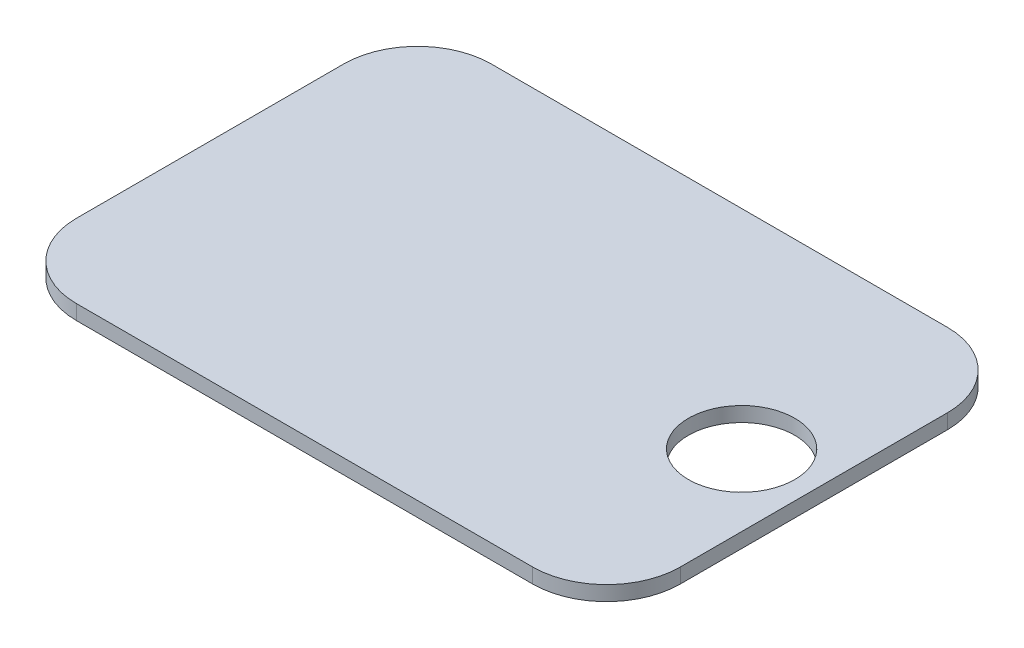
SolidWorks part; units mm, degrees
material "Acrylic (Medium-high impact)"
ref_plane "Front Plane" through (0, 0, 0) normal (0, 0, 1) x (1, 0, 0)
ref_plane "Top Plane" through (0, 0, 0) normal (0, 1, 0) x (1, 0, 0)
ref_plane "Right Plane" through (0, 0, 0) normal (1, 0, 0) x (0, 0, -1)
sketch "Sketch1" plane through (0, 0, 0) normal (0, 1, 0) x (1, 0, 0)
  line L1 (-5.1403, 10.0605) -> (25.7597, 10.0605)
  line L2 (-10.1403, 5.0605) -> (-10.1403, -13.0395)
  line L3 (-5.1403, -18.0395) -> (25.7597, -18.0395)
  line L4 (30.7597, 5.0605) -> (30.7597, -13.0395)
  arc A0 (25.7597, -18.0395) -> (30.7597, -13.0395) centre (25.7597, -13.0395) ccw
  arc A1 (25.7597, 10.0605) -> (30.7597, 5.0605) centre (25.7597, 5.0605) cw
  arc A2 (-10.1403, -13.0395) -> (-5.1403, -18.0395) centre (-5.1403, -13.0395) ccw
  arc A3 (-5.1403, 10.0605) -> (-10.1403, 5.0605) centre (-5.1403, 5.0605) ccw
  circle A4 centre (25.9097, -4.0395) radius 3.6
  point P6 (30.7597, -18.0395)
  point P9 (30.7597, 10.0605)
  point P14 (-10.1403, 10.0605)
  point P17 (29.5097, -4.0395)
  dimension "D3" = 5
  dimension "D4" = 7.2
  dimension "D1" = 28.1
  dimension "D2" = 40.9
  dimension "D5" = 14.1
  dimension "D6" = 4.85
extrude "Boss-Extrude1" add sketch "Sketch1" along normal blind 1
